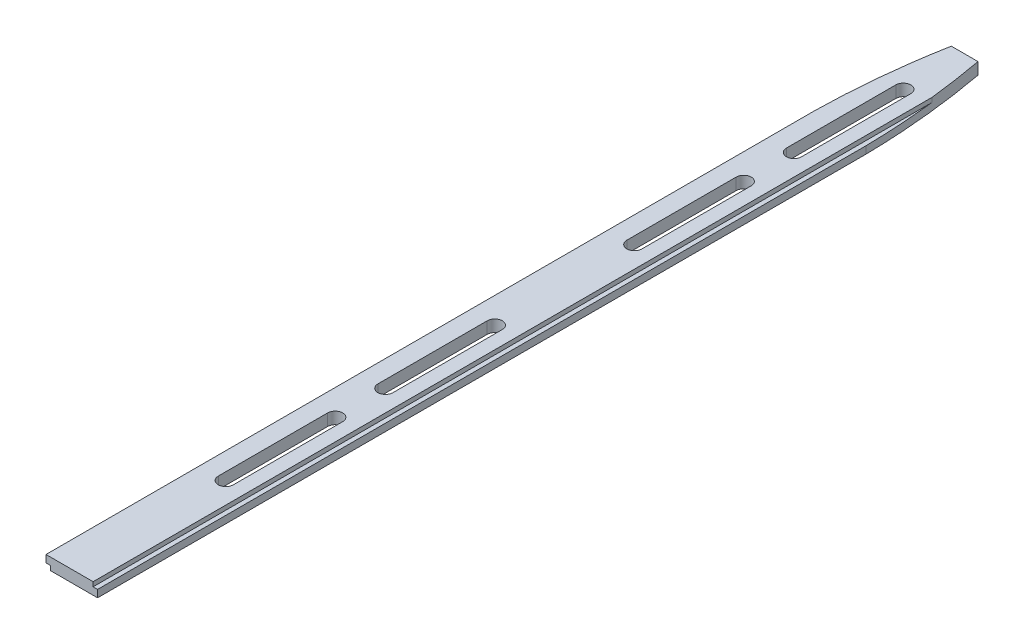
SolidWorks part; units mm, degrees
ref_plane "Ön Düzlem" through (0, 0, 0) normal (0, 0, 1) x (1, 0, 0)
ref_plane "Üst Düzlem" through (0, 0, 0) normal (0, 1, 0) x (1, 0, 0)
ref_plane "Sağ Düzlem" through (0, 0, 0) normal (1, 0, 0) x (0, 0, -1)
sketch "Çizim1" plane through (0, 0, 0) normal (0, 0, 1) x (1, 0, 0)
  line L1 (0, 0) -> (23.2, 0)
  line L2 (0, 0) -> (0, 7.3)
  line L3 (0, 7.3) -> (23.2, 7.3)
  line L4 (23.2, 0) -> (23.2, 7.3)
  dimension "D1" = 23.2
  dimension "D2" = 7.3
extrude "Yükseklik-Ekstrüzyon1" add sketch "Çizim1" along normal blind 401.7
sketch "Çizim2" plane through (0, 0, 401.7) normal (0, 0, 1) x (1, 0, 0)
  line L0 (23.2, 7.3) -> (0, 7.3) construction
  line L1 (21.2, 7.3) -> (23.2, 7.3)
  line L2 (21.2, 6.3) -> (21.2, 4.3)
  line L3 (21.2, 4.3) -> (23.2, 4.3)
  line L4 (23.2, 7.3) -> (23.2, 4.3)
  line L5 (23.2, 0) -> (23.2, 7.3) construction
  line L7 (0, 0) -> (2, 0)
  line L8 (0, 0) -> (0, 3)
  line L9 (0, 3) -> (2, 3)
  line L10 (2, 1) -> (2, 3)
  line L11 (23.2, 0) -> (2, 0)
  line L12 (23.2, 0) -> (23.2, 1)
  line L13 (23.2, 1) -> (2, 1)
  line L15 (0, 7.3) -> (21.2, 7.3)
  line L16 (0, 7.3) -> (0, 6.3)
  line L17 (0, 6.3) -> (21.2, 6.3)
  dimension "D1" = 2
  dimension "D2" = 3
  dimension "D3" = 3
  dimension "D4" = 2
  dimension "D5" = 1
  dimension "D6" = 1
extrude "Kes-Ekstrüzyon1" cut sketch "Çizim2" against normal blind 402.7
sketch "Çizim3" plane through (0, 6.3, 0) normal (0, 1, 0) x (1, 0, 0)
  line L0 (21.2, 0) -> (0, 0) construction
  line L7 (0, 0) -> (5.6, 0)
  line L8 (0, 0) -> (0, -56)
  line L14 (23.2, 0) -> (23.2, -56)
  line L15 (23.2, 0) -> (17.6, 0)
  spline S0 degree 2 poles (17.6, 0) (22.7794, -27.8813) (23.2, -56) knots 0 0 0 0.849777 0.849777 0.849777
  spline S1 degree 2 poles (5.6, 0) (0.4206, -27.8813) (0, -56) knots 0 0 0 0.849777 0.849777 0.849777
  dimension "D3" = 56
extrude "Kes-Ekstrüzyon2" cut sketch "Çizim3" against normal blind 402.7
sketch "Çizim4" plane through (0, 6.3, 0) normal (0, 1, 0) x (1, 0, 0)
  line L0 (17.6, 0) -> (5.6, 0) construction
  line L1 (8.2, -27.6) -> (8.2, -76.8)
  line L2 (15, -27.6) -> (15, -76.8)
  line L3 (8.2, -99.4) -> (8.2, -148.6)
  line L4 (15, -99.4) -> (15, -148.6)
  line L5 (8.2, -211.4) -> (8.2, -260.6)
  line L6 (15, -211.4) -> (15, -260.6)
  line L7 (8.2, -283.2) -> (8.2, -332.4)
  line L8 (15, -283.2) -> (15, -332.4)
  arc A0 (15, -27.6) -> (8.2, -27.6) centre (11.6, -27.6) ccw
  arc A1 (8.2, -76.8) -> (15, -76.8) centre (11.6, -76.8) ccw
  arc A2 (15, -99.4) -> (8.2, -99.4) centre (11.6, -99.4) ccw
  arc A3 (8.2, -148.6) -> (15, -148.6) centre (11.6, -148.6) ccw
  arc A4 (15, -211.4) -> (8.2, -211.4) centre (11.6, -211.4) ccw
  arc A5 (8.2, -260.6) -> (15, -260.6) centre (11.6, -260.6) ccw
  arc A6 (15, -283.2) -> (8.2, -283.2) centre (11.6, -283.2) ccw
  arc A7 (8.2, -332.4) -> (15, -332.4) centre (11.6, -332.4) ccw
  dimension "D2" = 6.8
  dimension "D3" = 6.8
  dimension "D5" = 6.8
  dimension "D6" = 6.8
  dimension "D9" = 6.8
  dimension "D10" = 6.8
  dimension "D13" = 6.8
  dimension "D15" = 6.8
  dimension "D1" = 27.6
  dimension "D4" = 49.2
  dimension "D7" = 22.6
  dimension "D8" = 49.2
  dimension "D11" = 62.8
  dimension "D12" = 49.2
  dimension "D14" = 22.6
  dimension "D16" = 49.2
extrude "Kes-Ekstrüzyon3" cut sketch "Çizim4" against normal blind 402.7
